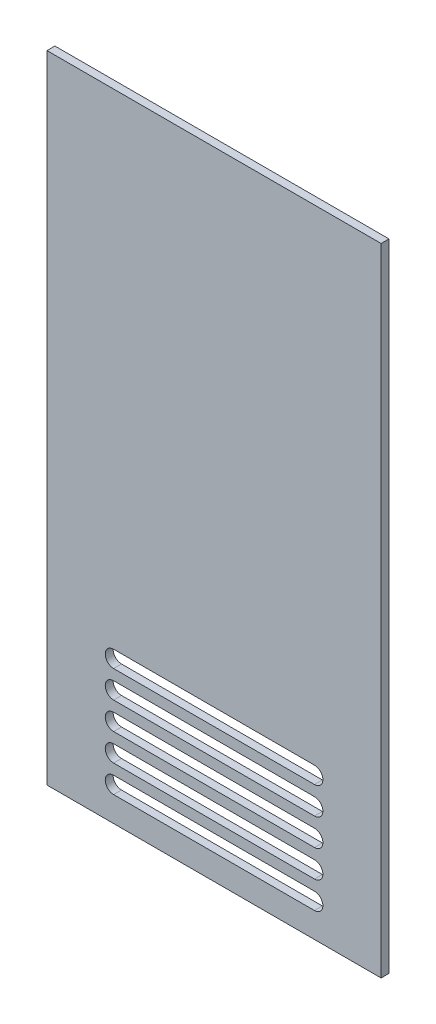
SolidWorks part; units mm, degrees
material "Acrylic (Medium-high impact)"
ref_plane "Front Plane" through (0, 0, 0) normal (0, 0, 1) x (1, 0, 0)
ref_plane "Top Plane" through (0, 0, 0) normal (0, 1, 0) x (1, 0, 0)
ref_plane "Right Plane" through (0, 0, 0) normal (1, 0, 0) x (0, 0, -1)
sketch "Sketch1" plane through (0, 0, 0) normal (0, 0, 1) x (1, 0, 0)
  line L1 (63.373, -120.65) -> (-63.373, -120.65)
  line L2 (63.373, -120.65) -> (63.373, 120.65)
  line L3 (63.373, 120.65) -> (-63.373, 120.65)
  line L4 (-63.373, -120.65) -> (-63.373, 120.65)
  line L5 (63.373, -120.65) -> (-63.373, 120.65) construction
  line L6 (63.373, 120.65) -> (-63.373, -120.65) construction
  point P0 (0, 0)
  dimension "D1" = 241.3
  dimension "D2" = 126.746
extrude "Boss-Extrude1" add sketch "Sketch1" along normal blind 2.9972
sketch "Sketch2" plane through (0, 0, 2.9972) normal (0, 0, 1) x (1, 0, 0)
  line L0 (-38.1, -66.55) -> (38.1, -66.55) construction
  line L1 (-38.1, -63.375) -> (38.1, -63.375)
  line L2 (-38.1, -69.725) -> (38.1, -69.725)
  line L3 (-38.1, -87.25) -> (38.1, -87.25) construction
  line L4 (-38.1, -84.075) -> (38.1, -84.075)
  line L5 (-38.1, -90.425) -> (38.1, -90.425)
  line L6 (-38.1, -107.95) -> (38.1, -107.95) construction
  line L7 (-38.1, -104.775) -> (38.1, -104.775)
  line L8 (-38.1, -111.125) -> (38.1, -111.125)
  line L9 (-38.1, -76.9) -> (38.1, -76.9) construction
  line L10 (-38.1, -73.725) -> (38.1, -73.725)
  line L11 (-38.1, -80.075) -> (38.1, -80.075)
  line L12 (-38.1, -97.6) -> (38.1, -97.6) construction
  line L13 (-38.1, -94.425) -> (38.1, -94.425)
  line L14 (-38.1, -100.775) -> (38.1, -100.775)
  line L15 (0, -69.725) -> (0, -73.725) construction
  line L16 (0, -80.075) -> (0, -84.075) construction
  line L17 (0, -90.425) -> (0, -94.425) construction
  line L18 (0, -100.775) -> (0, -104.775) construction
  line L19 (-63.373, -120.65) -> (63.373, -120.65) construction
  arc A0 (-38.1, -63.375) -> (-38.1, -69.725) centre (-38.1, -66.55) ccw
  arc A1 (38.1, -69.725) -> (38.1, -63.375) centre (38.1, -66.55) ccw
  arc A2 (-38.1, -84.075) -> (-38.1, -90.425) centre (-38.1, -87.25) ccw
  arc A3 (38.1, -90.425) -> (38.1, -84.075) centre (38.1, -87.25) ccw
  arc A4 (-38.1, -104.775) -> (-38.1, -111.125) centre (-38.1, -107.95) ccw
  arc A5 (38.1, -111.125) -> (38.1, -104.775) centre (38.1, -107.95) ccw
  arc A6 (-38.1, -73.725) -> (-38.1, -80.075) centre (-38.1, -76.9) ccw
  arc A7 (38.1, -80.075) -> (38.1, -73.725) centre (38.1, -76.9) ccw
  arc A8 (-38.1, -94.425) -> (-38.1, -100.775) centre (-38.1, -97.6) ccw
  arc A9 (38.1, -100.775) -> (38.1, -94.425) centre (38.1, -97.6) ccw
  point P2 (0, -66.55)
  point P7 (0, -87.25)
  point P14 (0, -107.95)
  point P21 (0, -76.9)
  point P31 (0, -97.6)
  dimension "D1" = 3.175
  dimension "D2" = 4
  dimension "D3" = 9.525
  dimension "D4" = 76.2
extrude "Cut-Extrude1" cut sketch "Sketch2" against normal through all
